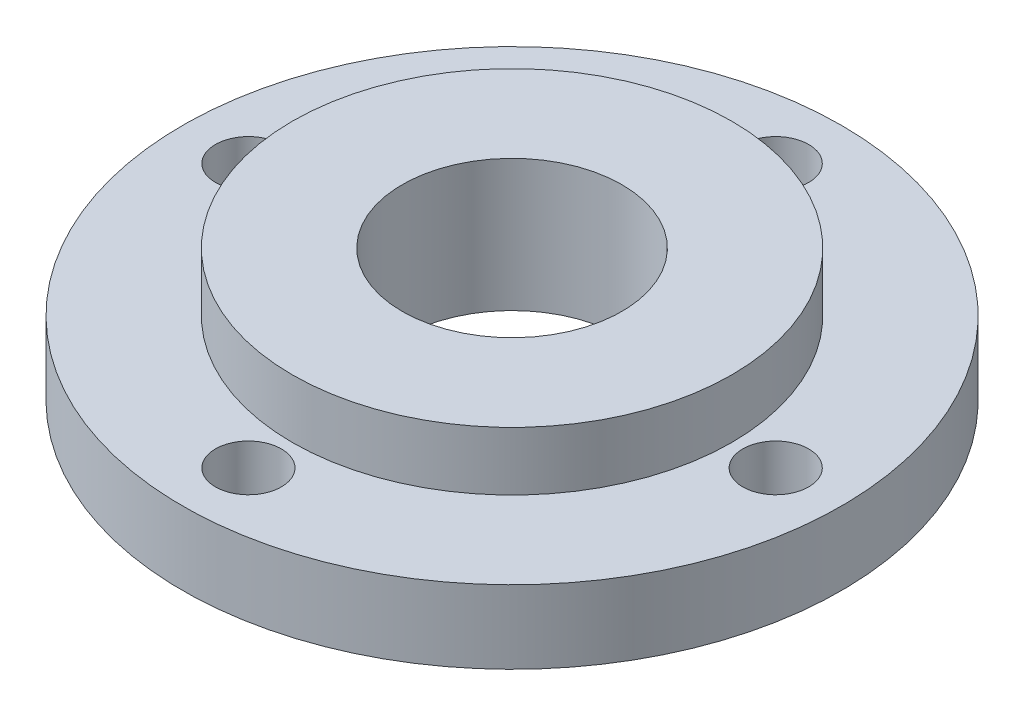
SolidWorks part; units mm, degrees
ref_plane "前视基准面" through (0, 0, 0) normal (0, 0, 1) x (1, 0, 0)
ref_plane "上视基准面" through (0, 0, 0) normal (0, 1, 0) x (1, 0, 0)
ref_plane "右视基准面" through (0, 0, 0) normal (1, 0, 0) x (0, 0, -1)
other "Configuration Table"
sketch "草图1" plane through (0, 0, 0) normal (0, 0, 1) x (1, 0, 0)
  line L0 (0, -10) -> (0, 25) construction
  line L1 (15, 0) -> (45, 0)
  line L2 (45, 0) -> (45, 10)
  line L3 (45, 10) -> (30, 10)
  line L4 (30, 10) -> (30, 18)
  line L5 (30, 18) -> (15, 18)
  line L6 (15, 18) -> (15, 0)
revolve "旋转1" add sketch "草图1" angle 360 about L0
sketch "草图2" plane through (0, 0, 0) normal (0, 1, 0) x (1, 0, 0)
  circle A0 centre (36, 0) radius 4.5
  circle A1 centre (0, 36) radius 4.5
  circle A2 centre (-36, 0) radius 4.5
  circle A3 centre (0, -36) radius 4.5
extrude "切除-拉伸1" cut sketch "草图2" along normal through all
